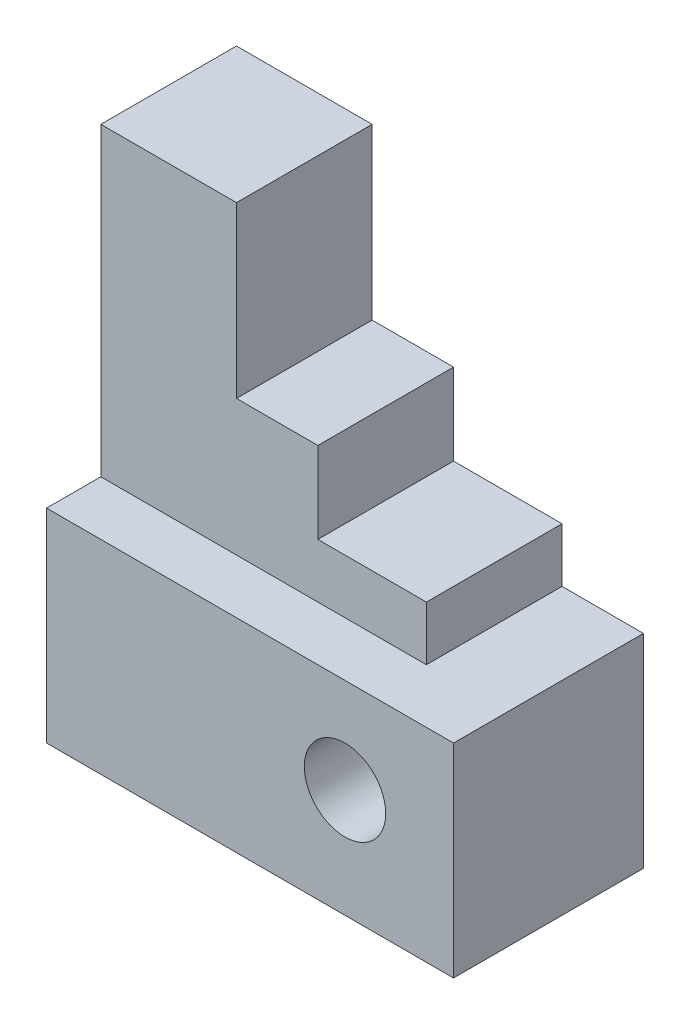
SolidWorks part; units mm, degrees
ref_plane "Front Plane" through (0, 0, 0) normal (0, 0, 1) x (1, 0, 0)
ref_plane "Top Plane" through (0, 0, 0) normal (0, 1, 0) x (1, 0, 0)
ref_plane "Right Plane" through (0, 0, 0) normal (1, 0, 0) x (0, 0, -1)
sketch "Sketch1" plane through (0, 0, 0) normal (0, 1, 0) x (1, 0, 0)
  line L1 (0, 0) -> (60, 0)
  line L2 (0, 0) -> (0, -28)
  line L3 (0, -28) -> (60, -28)
  line L4 (60, 0) -> (60, -28)
  dimension "D1" = 28
  dimension "D2" = 60
extrude "Boss-Extrude1" add sketch "Sketch1" along normal blind 30
sketch "Sketch2" plane through (0, 30, 0) normal (0, 1, 0) x (1, 0, 0)
  line L1 (0, 0) -> (48, 0)
  line L2 (0, 0) -> (0, -20)
  line L3 (0, -20) -> (48, -20)
  line L4 (48, 0) -> (48, -20)
  dimension "D1" = 20
  dimension "D2" = 48
extrude "Boss-Extrude2" add sketch "Sketch2" along normal blind 8
sketch "Sketch3" plane through (0, 38, 0) normal (0, 1, 0) x (1, 0, 0)
  line L0 (0, -20) -> (48, -20) construction
  line L1 (0, 0) -> (32, 0)
  line L2 (0, 0) -> (0, -20)
  line L3 (0, -20) -> (32, -20)
  line L4 (32, 0) -> (32, -20)
  dimension "D1" = 32
extrude "Boss-Extrude3" add sketch "Sketch3" along normal blind 12
sketch "Sketch4" plane through (0, 50, 0) normal (0, 1, 0) x (1, 0, 0)
  line L0 (0, -20) -> (48, -20) construction
  line L1 (0, 0) -> (20, 0)
  line L2 (0, 0) -> (0, -20)
  line L3 (0, -20) -> (20, -20)
  line L4 (20, 0) -> (20, -20)
  dimension "D1" = 20
extrude "Boss-Extrude4" add sketch "Sketch4" along normal blind 25
sketch "Sketch5" plane through (0, 0, 28) normal (0, 0, 1) x (1, 0, 0)
  line L0 (60, 30) -> (60, 0) construction
  line L1 (0, 0) -> (60, 0) construction
  circle A0 centre (44, 16) radius 6
  dimension "D3" = 12
  dimension "D1" = 16
  dimension "D2" = 16
extrude "Cut-Extrude1" cut sketch "Sketch5" against normal through all
